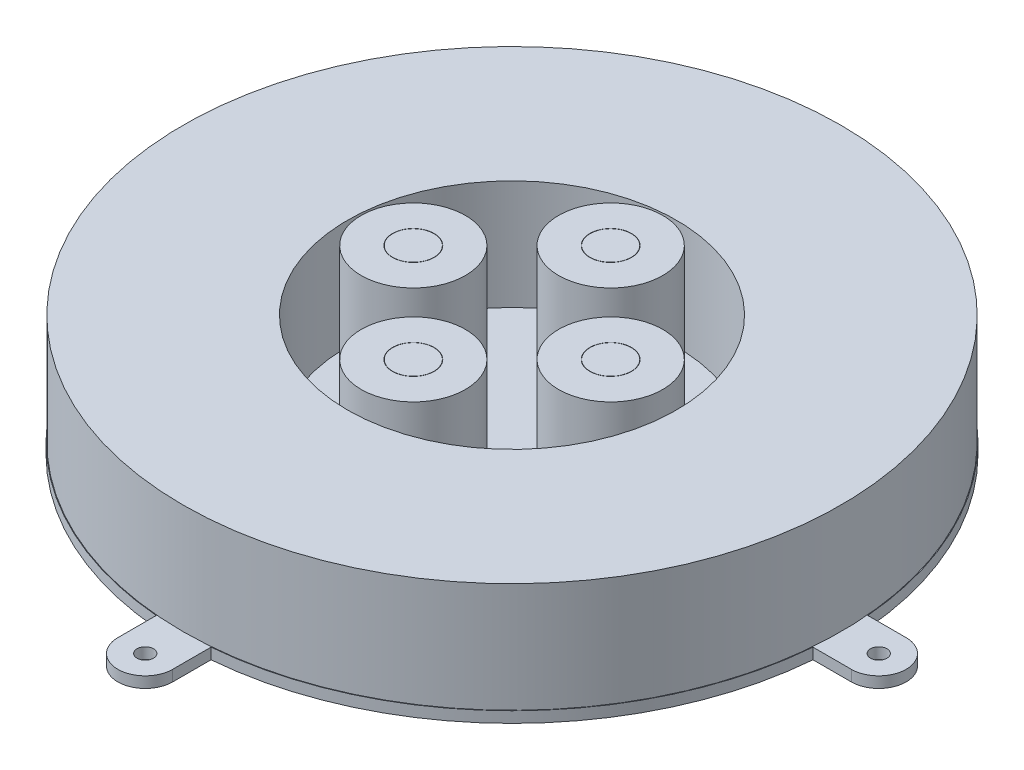
SolidWorks part; units mm, degrees
ref_plane "Front Plane" through (0, 0, 0) normal (0, 0, 1) x (1, 0, 0)
ref_plane "Top Plane" through (0, 0, 0) normal (0, 1, 0) x (1, 0, 0)
ref_plane "Right Plane" through (0, 0, 0) normal (1, 0, 0) x (0, 0, -1)
sketch "Sketch1" plane through (0, 0, 0) normal (0, 1, 0) x (1, 0, 0)
  circle A0 centre (0, 0) radius 60
  circle A1 centre (0, 0) radius 30
  dimension "D1" = 120
  dimension "D2" = 60
extrude "Boss-Extrude1" add sketch "Sketch1" along normal mid plane 20
sketch "Sketch2" plane through (0, -10, 0) normal (0, -1, 0) x (1, 0, 0)
  line L0 (-5, 66.8917) -> (-5, 59.8917)
  line L1 (0, 0) -> (0, 101.8852) construction
  line L2 (5, 66.8917) -> (5, 59.8917)
  line L4 (5, 59.8917) -> (14.9448, 59.8917) construction
  line L6 (66.8917, -5) -> (59.8917, -5)
  line L7 (66.8917, 5) -> (59.8917, 5)
  line L9 (-5, -66.8917) -> (-5, -59.8917)
  line L10 (5, -66.8917) -> (5, -59.8917)
  line L12 (-66.8917, 5) -> (-59.8917, 5)
  line L13 (-66.8917, -5) -> (-59.8917, -5)
  arc A0 (-59.8917, -5) -> (-5, -59.8917) centre (0, 0) ccw
  arc A1 (-5, 66.8917) -> (5, 66.8917) centre (0, 66.8917) cw
  circle A2 centre (0, 66.8917) radius 1.5
  arc A3 (66.8917, 5) -> (66.8917, -5) centre (66.8917, 0) cw
  circle A4 centre (66.8917, 0) radius 1.5
  arc A5 (5, -66.8917) -> (-5, -66.8917) centre (0, -66.8917) cw
  circle A6 centre (0, -66.8917) radius 1.5
  arc A7 (-66.8917, -5) -> (-66.8917, 5) centre (-66.8917, 0) cw
  circle A8 centre (-66.8917, 0) radius 1.5
  arc A9 (59.8917, 5) -> (5, 59.8917) centre (0, 0) ccw
  arc A10 (-5, 59.8917) -> (-59.8917, 5) centre (0, 0) ccw
  arc A11 (5, -59.8917) -> (59.8917, -5) centre (0, 0) ccw
  point P33 (0, 0)
  dimension "D1" = 120.2
  dimension "D2" = 10
  dimension "D4" = 3
  dimension "D3" = 7
  dimension "D5" = 4
extrude "Boss-Extrude2" add sketch "Sketch2" along normal blind 2 separate body
sketch "Sketch3" plane through (0, -10, 0) normal (0, 1, 0) x (1, 0, 0)
  circle A0 centre (0, 18) radius 3.75
  circle A1 centre (0, 18) radius 9.5
  circle A2 centre (0, 18) radius 3.8
  circle A3 centre (18, 0) radius 3.75
  circle A4 centre (18, 0) radius 9.5
  circle A5 centre (18, 0) radius 3.8
  circle A6 centre (0, -18) radius 3.75
  circle A7 centre (0, -18) radius 9.5
  circle A8 centre (0, -18) radius 3.8
  circle A9 centre (-18, 0) radius 3.75
  circle A10 centre (-18, 0) radius 9.5
  circle A11 centre (-18, 0) radius 3.8
  point P20 (0, 0)
  dimension "D1" = 7.5
  dimension "D2" = 19
  dimension "D3" = 7.6
  dimension "D4" = 18
  dimension "D5" = 4
extrude "Boss-Extrude3" add sketch "Sketch3" along normal blind 22 separate body contours A1 A2 | A10 A11 | A9 | A7 A8 | A6 | A3 | A4 A5 | A0
